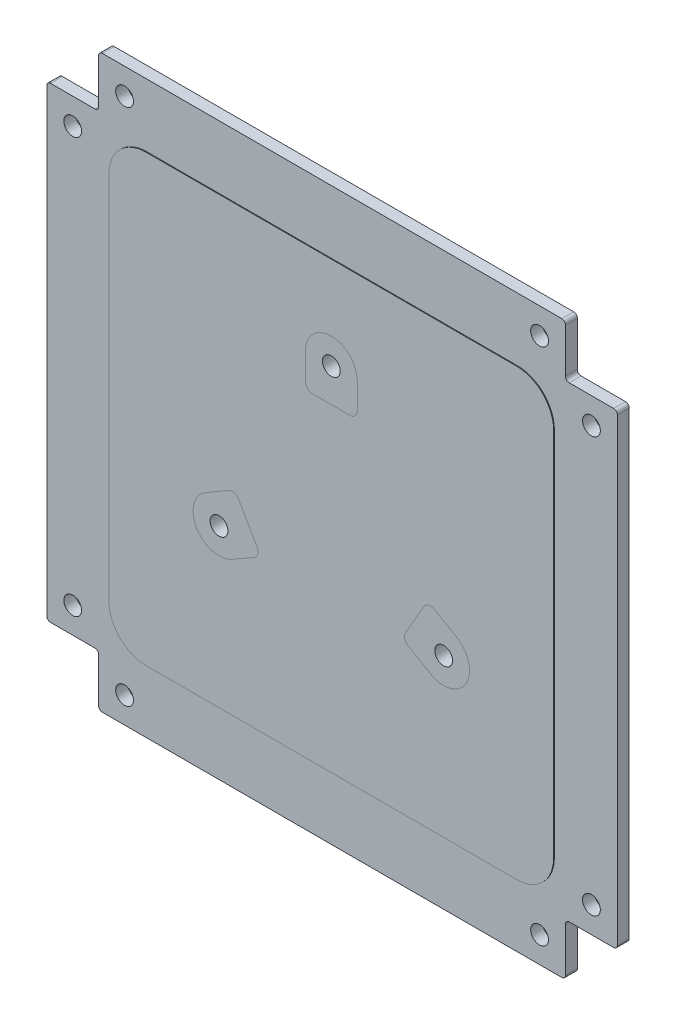
SolidWorks part; units mm, degrees
material "PET"
ref_plane "Front Plane" through (0, 0, 0) normal (0, 0, 1) x (1, 0, 0)
ref_plane "Top Plane" through (0, 0, 0) normal (0, 1, 0) x (1, 0, 0)
ref_plane "Right Plane" through (0, 0, 0) normal (1, 0, 0) x (0, 0, -1)
sketch "Sketch1" plane through (0, 0, 0) normal (0, 0, 1) x (1, 0, 0)
  line L0 (-31.5, 38) -> (-31.5, 32)
  line L1 (-31, -38.5) -> (31, -38.5)
  line L2 (-38.5, 31) -> (-38.5, -31)
  line L3 (-31, 38.5) -> (31, 38.5)
  line L4 (38.5, -31) -> (38.5, 31)
  line L5 (31.5, -38) -> (31.5, -32)
  line L6 (32, -31.5) -> (38, -31.5)
  line L7 (-32, 31.5) -> (-38, 31.5)
  line L8 (31.5, 38) -> (31.5, 32)
  line L9 (32, 31.5) -> (38, 31.5)
  line L10 (-38, -31.5) -> (-32, -31.5)
  line L11 (-31.5, -32) -> (-31.5, -38)
  line L12 (-32, -32) -> (32, 32) construction
  line L13 (32, -32) -> (-32, 32) construction
  arc A0 (-31, 38.5) -> (-31.5, 38) centre (-31, 38) ccw
  arc A1 (31, 38.5) -> (31.5, 38) centre (31, 38) cw
  arc A2 (31.5, 32) -> (32, 31.5) centre (32, 32) ccw
  arc A3 (38, 31.5) -> (38.5, 31) centre (38, 31) cw
  arc A4 (31, -38.5) -> (31.5, -38) centre (31, -38) ccw
  arc A5 (32, -31.5) -> (31.5, -32) centre (32, -32) ccw
  arc A6 (38, -31.5) -> (38.5, -31) centre (38, -31) ccw
  arc A7 (-31.5, -38) -> (-31, -38.5) centre (-31, -38) ccw
  arc A8 (-31.5, -32) -> (-32, -31.5) centre (-32, -32) ccw
  arc A9 (-38.5, -31) -> (-38, -31.5) centre (-38, -31) ccw
  arc A10 (-38, 31.5) -> (-38.5, 31) centre (-38, 31) ccw
  arc A11 (-32, 31.5) -> (-31.5, 32) centre (-32, 32) ccw
  point P0 (0, 0)
  dimension "D4" = 0.5
  dimension "D1" = 7
  dimension "D2" = 7
  dimension "D3" = 7
  dimension "D5" = 7
  dimension "D6" = 7
  dimension "D7" = 7
  dimension "D8" = 7
  dimension "D9" = 7
  dimension "D10" = 77
  dimension "D11" = 77
extrude "Boss-Extrude1" add sketch "Sketch1" along normal blind 1.6
sketch "Esboço1" plane through (0, 0, 1.6) normal (0, 0, 1) x (1, 0, 0)
  line L1 (-25, -30) -> (25, -30)
  line L2 (-30, -25) -> (-30, 25)
  line L3 (-25, 30) -> (25, 30)
  line L4 (30, -25) -> (30, 25)
  line L5 (-25, -25) -> (25, 25) construction
  line L6 (-25, 25) -> (25, -25) construction
  arc A0 (-30, 25) -> (-25, 30) centre (-25, 25) cw
  arc A1 (25, 30) -> (30, 25) centre (25, 25) cw
  arc A2 (30, -25) -> (25, -30) centre (25, -25) cw
  arc A3 (-25, -30) -> (-30, -25) centre (-25, -25) cw
  point P0 (0, 0)
  dimension "D1" = 5
  dimension "D2" = 60
  dimension "D3" = 60
extrude "Boss-Extrude2" add sketch "Esboço1" along normal blind 0.1
hole_wizard "M2 Hole1-FixingStructure" positions "Sketch3" profile "Sketch2" hole size "M2" standard "DIN"
sketch "Sketch3" plane through (0, 0, 0) normal (0, 0, -1) x (-1, 0, 0)
  line L0 (-31, 38.5) -> (31, 38.5) construction
  line L1 (31, -38.5) -> (-31, -38.5) construction
  line L2 (-38.5, -31) -> (-38.5, 31) construction
  line L3 (38.5, 31) -> (38.5, -31) construction
  line L4 (-31, 38.5) -> (31, 38.5) construction
  line L5 (31, -38.5) -> (-31, -38.5) construction
  line L6 (38.5, 31) -> (38.5, -31) construction
  line L7 (-38.5, -31) -> (-38.5, 31) construction
  point P0 (-28, 35)
  point P2 (28, 35)
  point P4 (-28, -35)
  point P6 (28, -35)
  point P20 (35, 28)
  point P22 (35, -28)
  point P24 (-35, -28)
  point P26 (-35, 28)
  dimension "D1" = 3.5
  dimension "D2" = 3.5
  dimension "D3" = 10.5
  dimension "D4" = 10.5
  dimension "D5" = 10.5
  dimension "D6" = 10.5
  dimension "D7" = 3.5
  dimension "D8" = 3.5
sketch "Sketch2" plane through (28, 35, 0) normal (1, 0, 0) x (0, 1, 0)
  line L0 (0, 0) -> (0, 200.721)
  line L1 (0, 200.721) -> (1.2, 200)
  line L2 (1.2, 200) -> (1.2, 0)
  line L5 (1.2, 0) -> (0, 0)
  line L10 (0, 200.721) -> (-1.2, 200) construction
  line L11 (0, -6.35) -> (0, 107.95) construction
  dimension "Hole Dia." = 2.4
  dimension "Hole Depth" = 200
  dimension "Drill Angle" = 118
sketch "Sketch4" plane through (0, 0, 1.7) normal (0, 0, 1) x (1, 0, 0)
  circle A0 centre (-15.1554, -8.75) radius 1.2 construction
  circle A1 centre (15.1554, -8.75) radius 1.2 construction
  circle A2 centre (0, 17.5) radius 1.2 construction
  circle A3 centre (-15.1554, -8.75) radius 1.2
  circle A4 centre (15.1554, -8.75) radius 1.2
  circle A5 centre (0, 17.5) radius 1.2
extrude "Cut-Extrude1" cut sketch "Sketch4" against normal up to surface (1.7 mm away) up to face at (26.8, 35, 0)
sketch "Sketch5" plane through (0, 0, 1.7) normal (0, 0, 1) x (1, 0, 0)
  line L5 (-10.3744, -10.0311) -> (-13.4054, -11.7811)
  line L6 (14.7404, -4.4689) -> (16.9054, -5.7189)
  line L7 (13.4054, -11.7811) -> (11.2404, -10.5311)
  line L8 (13.8744, -3.9689) -> (16.9054, -5.7189)
  line L9 (13.4054, -11.7811) -> (10.3744, -10.0311)
  line L10 (10.0083, -8.6651) -> (12.5083, -4.3349)
  line L11 (10.0083, -8.6651) -> (12.5083, -4.3349)
  line L12 (-16.9054, -5.7189) -> (-13.8744, -3.9689)
  line L13 (-12.5083, -4.3349) -> (-10.0083, -8.6651)
  line L14 (-3.5, 14) -> (-3.5, 17.5)
  line L15 (3.5, 17.5) -> (3.5, 14)
  line L16 (2.5, 13) -> (-2.5, 13)
  arc A2 (10.3744, -10.0311) -> (10.0083, -8.6651) centre (10.8744, -9.1651) cw
  arc A3 (13.4054, -11.7811) -> (16.9054, -5.7189) centre (15.1554, -8.75) ccw
  arc A4 (13.4054, -11.7811) -> (16.9054, -5.7189) centre (15.1554, -8.75) ccw
  arc A5 (13.8744, -3.9689) -> (12.5083, -4.3349) centre (13.3744, -4.8349) ccw
  arc A6 (-13.8744, -3.9689) -> (-12.5083, -4.3349) centre (-13.3744, -4.8349) cw
  arc A7 (-16.9054, -5.7189) -> (-13.4054, -11.7811) centre (-15.1554, -8.75) ccw
  arc A8 (-10.3744, -10.0311) -> (-10.0083, -8.6651) centre (-10.8744, -9.1651) ccw
  arc A9 (3.5, 14) -> (2.5, 13) centre (2.5, 14) cw
  arc A10 (3.5, 17.5) -> (-3.5, 17.5) centre (0, 17.5) ccw
  arc A11 (-3.5, 14) -> (-2.5, 13) centre (-2.5, 14) ccw
  point P34 (0, 0)
  dimension "D3" = 1
  dimension "D1" = 1
  dimension "D2" = 1
  dimension "D4" = 3
split line "Split Line1"
